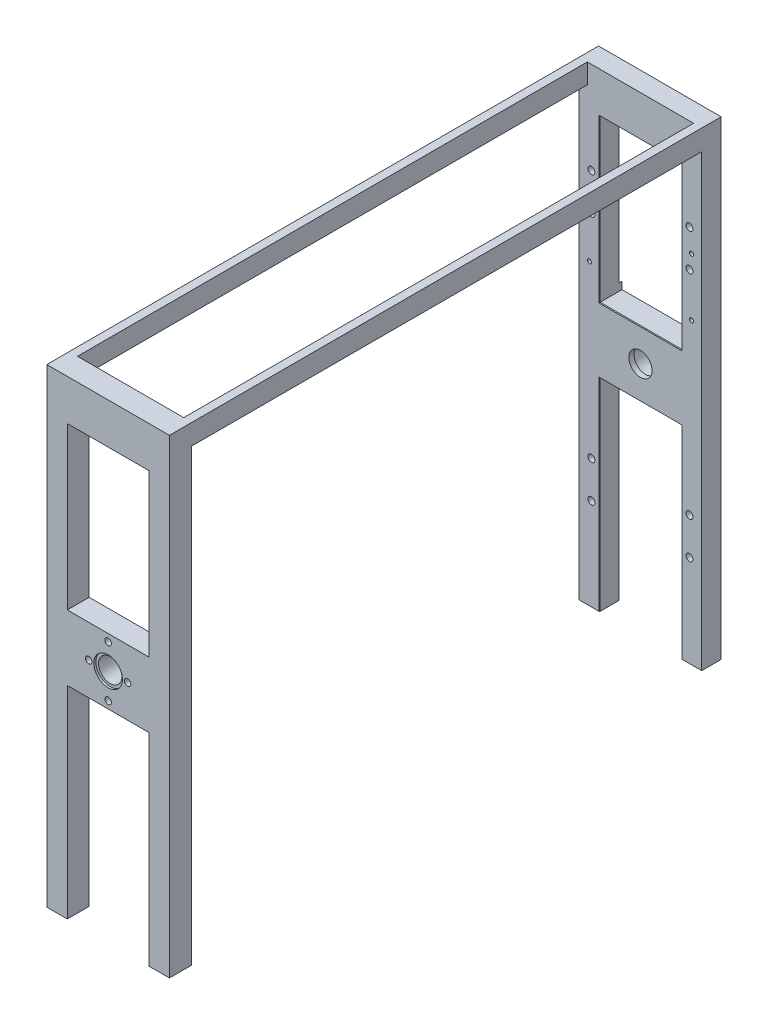
SolidWorks part; units mm, degrees
ref_plane "Front Plane" through (0, 0, 0) normal (0, 0, 1) x (1, 0, 0)
ref_plane "Top Plane" through (0, 0, 0) normal (0, 1, 0) x (1, 0, 0)
ref_plane "Right Plane" through (0, 0, 0) normal (1, 0, 0) x (0, 0, -1)
sketch "Sketch1" plane through (0, 0, 0) normal (0, 0, 1) x (1, 0, 0)
  line L1 (-30, -115) -> (30, -115)
  line L2 (-30, -115) -> (-30, 115)
  line L3 (-30, 115) -> (30, 115)
  line L4 (30, -115) -> (30, 115)
  line L5 (-30, -115) -> (30, 115) construction
  line L6 (-30, 115) -> (30, -115) construction
  point P0 (0, 0)
  dimension "D1" = 60
  dimension "D2" = 230
extrude "Boss-Extrude1" add sketch "Sketch1" along normal blind 11 from offset 8 offset against normal yes
sketch "Sketch2" plane through (0, 0, 0) normal (0, 0, 1) x (1, 0, 0)
  line L0 (30, -115) -> (30, 115) construction
  line L1 (-20, -16) -> (20, -16)
  line L2 (-20, -16) -> (-20, -115)
  line L3 (-20, -115) -> (20, -115)
  line L4 (20, -16) -> (20, -115)
  line L5 (-30, 115) -> (-30, -115) construction
  line L6 (-30, -115) -> (30, -115) construction
  dimension "D1" = 10
  dimension "D2" = 10
  dimension "D3" = 0
  dimension "D4" = 99
extrude "Cut-Extrude1" cut sketch "Sketch2" along normal through all both and the other way through all
sketch "Sketch3" plane through (0, 0, 0) normal (0, 0, 1) x (1, 0, 0)
  line L0 (30, -115) -> (30, 115) construction
  line L1 (-20, 16) -> (20, 16)
  line L2 (-20, 16) -> (-20, 95)
  line L3 (-20, 95) -> (20, 95)
  line L4 (20, 16) -> (20, 95)
  line L5 (-20, 16) -> (20, 95) construction
  line L6 (-20, 95) -> (20, 16) construction
  point P0 (0, 55.5)
  dimension "D1" = 40
  dimension "D2" = 10
  dimension "D3" = 16
  dimension "D4" = 79
extrude "Cut-Extrude2" cut sketch "Sketch3" along normal through all both and the other way through all
ref_plane "Plane16" through (0, 0, 252.5) normal (0, 0, 1) x (1, 0, 0)
sketch "Sketch4" plane through (0, 0, 252.5) normal (0, 0, 1) x (1, 0, 0)
  line L1 (-30, -115) -> (30, -115)
  line L2 (-30, -115) -> (-30, 115)
  line L3 (-30, 115) -> (30, 115)
  line L4 (30, -115) -> (30, 115)
  line L5 (-30, -115) -> (30, 115) construction
  line L6 (-30, 115) -> (30, -115) construction
  point P0 (0, 0)
  dimension "D1" = 60
  dimension "D2" = 230
extrude "Boss-Extrude3" add sketch "Sketch4" along normal blind 11 separate body
sketch "Sketch6" plane through (0, 0, 263.5) normal (0, 0, 1) x (1, 0, 0)
  line L1 (-20, 16) -> (20, 16)
  line L2 (-20, 16) -> (-20, 95)
  line L3 (-20, 95) -> (20, 95)
  line L4 (20, 16) -> (20, 95)
  line L5 (-20, 16) -> (20, 95) construction
  line L6 (-20, 95) -> (20, 16) construction
  line L7 (30, -115) -> (30, 115) construction
  point P0 (0, 55.5)
  dimension "D1" = 40
  dimension "D2" = 10
  dimension "D3" = 16
  dimension "D4" = 79
extrude "Cut-Extrude3" cut sketch "Sketch6" against normal through all both and the other way through all
sketch "Sketch7" plane through (0, 0, 252.5) normal (0, 0, 1) x (1, 0, 0)
  line L0 (-20, -16) -> (20, -16)
  line L1 (-20, -16) -> (-20, -115)
  line L2 (-20, -115) -> (20, -115)
  line L3 (20, -16) -> (20, -115)
  line L4 (30, -115) -> (30, 115) construction
  line L5 (-30, -115) -> (30, -115) construction
  dimension "D1" = 99
  dimension "D2" = 10
  dimension "D3" = 40
  dimension "D4" = 0
extrude "Cut-Extrude4" cut sketch "Sketch7" along normal through all both and the other way through all
sketch "Sketch8" plane through (0, 0, 3) normal (0, 0, 1) x (1, 0, 0)
  line L0 (-30, 115) -> (-30, -115) construction
  line L1 (-30, 105) -> (-26, 105)
  line L2 (-30, 105) -> (-30, 115)
  line L3 (-30, 115) -> (-26, 115)
  line L4 (-26, 105) -> (-26, 115)
  line L5 (0, -126.5) -> (0, 126.5) construction
  line L6 (26, 105) -> (26, 115)
  line L7 (30, 115) -> (26, 115)
  line L8 (30, 105) -> (30, 115)
  line L9 (30, 105) -> (26, 105)
  dimension "D1" = 4
  dimension "D2" = 10
  dimension "D3" = 105
extrude "Boss-Extrude4" add sketch "Sketch8" along direction (0, 0, -1) on the side of the normal up to surface (249.5 mm away)
sketch "Sketch9" plane through (0, 0, 252.5) normal (0, 0, 1) x (1, 0, 0)
  circle A0 centre (0, 0) radius 6.5
extrude "Cut-Extrude13" cut sketch "Sketch9" along normal through all both and the other way through all
sketch "Sketch13" plane through (0, 0, 252.5) normal (0, 0, -1) x (-1, 0, 0)
  circle A0 centre (0, 0) radius 7
extrude "Cut-Extrude15" cut sketch "Sketch13" against normal blind 1 from offset 10 offset against normal yes
sketch "Sketch14" plane through (0, 0, -8) normal (0, 0, -1) x (-1, 0, 0)
  circle A0 centre (0, 0) radius 7
extrude "Cut-Extrude16" cut sketch "Sketch14" against normal blind 1
sketch "Sketch15" plane through (0, 0, 263.5) normal (0, 0, 1) x (1, 0, 0)
  line L0 (0, -126.5) -> (0, 126.5) construction
  line L1 (33, 0) -> (-33, 0) construction
  circle A4 centre (9.5, 0) radius 1.6
  circle A5 centre (-9.5, 0) radius 1.6
  circle A6 centre (0, 12.5) radius 1.6
  circle A7 centre (0, -12.5) radius 1.6
  point P11 (0, 0)
extrude "Cut-Extrude17" cut sketch "Sketch15" against normal up to next
sketch "Sketch17" plane through (0, 0, -8) normal (0, 0, -1) x (-1, 0, 0)
  line L0 (0, 126.5) -> (0, -126.5) construction
  line L1 (20, 62) -> (30, 62)
  line L2 (20, 62) -> (20, 28)
  line L3 (20, 28) -> (30, 28)
  line L4 (30, 62) -> (30, 28)
  line L5 (20, 62) -> (30, 28) construction
  line L6 (20, 28) -> (30, 62) construction
  line L7 (-20, 28) -> (-30, 28)
  line L8 (-30, 62) -> (-30, 28)
  line L9 (-20, 62) -> (-30, 62)
  line L10 (-20, 62) -> (-20, 28)
  point P0 (25, 45)
  dimension "D1" = 45
  dimension "D2" = 25
  dimension "D3" = 10
  dimension "D4" = 34
extrude "Boss-Extrude5" add sketch "Sketch17" along normal blind 6
sketch "Sketch18" plane through (0, 0, -14) normal (0, 0, -1) x (-1, 0, 0)
  line L0 (-30, 28) -> (-20, 28) construction
  line L1 (-20, 62) -> (-30, 62) construction
  line L2 (-30, -115) -> (-30, 28) construction
  line L3 (-20, 16) -> (-20, 28) construction
  line L4 (0, 126.5) -> (0, -126.5) construction
  line L5 (-30, 28) -> (-20, 28) construction
  line L6 (20, 16) -> (-20, 16) construction
  circle A0 centre (-25, 59.2) radius 1
  circle A1 centre (-25, 31) radius 1
  circle A2 centre (25, 59.2) radius 1
  circle A3 centre (25, 31) radius 1
  dimension "D5" = 28.2
  dimension "D1" = 28
  dimension "D2" = 34
  dimension "D3" = 10
  dimension "D4" = 30
  dimension "D6" = 12
  dimension "D7" = 15
extrude "Cut-Extrude18" cut sketch "Sketch18" against normal up to next
chamfer "Chamfer1" distance 0.3 angle 45 1 edges at (-30, -5, 252.5)
chamfer "Chamfer2" distance 0.3 angle 45 1 edges at (30, -5, 252.5)
chamfer "Chamfer3" distance 0.3 angle 45 2 edges at (-26, 105, 127.75) (26, 105, 127.75)
chamfer "Chamfer4" distance 0.3 angle 45 7 edges at (0, 16, 3) (-20, 55.5, 3) (0, 95, 3) (20, 55.5, 3) (20, -65.5, 3) (0, -16, 3) (-20, -65.5, 3)
chamfer "Chamfer5" distance 0.3 angle 45 7 edges at (-20, -65.5, 252.5) (20, -65.5, 252.5) (0, -16, 252.5) (0, 95, 252.5) (-20, 55.5, 252.5) (0, 16, 252.5) (20, 55.5, 252.5)
sketch "Sketch19" plane through (0, 0, 0) normal (0, 0, 1) x (1, 0, 0)
  circle A0 centre (0, 0) radius 10
  circle A1 centre (0, 0) radius 6.5
extrude "Upper_Bearing_Housing_Extension" add sketch "Sketch19" along normal blind 3.9 from offset 248.7
sketch "Sketch20" plane through (0, 0, 0) normal (0, 0, 1) x (1, 0, 0)
  circle A0 centre (0, 0) radius 6.51
  circle A1 centre (0, 0) radius 5.7
extrude "Lower_Bearing_Outer_Race_Shoulder" add sketch "Sketch20" along normal blind 2.5 from offset 0.5
sketch "Sketch21" plane through (0, 0, 0) normal (0, 0, 1) x (1, 0, 0)
  circle A0 centre (0, 0) radius 6.51
  circle A1 centre (0, 0) radius 5.7
extrude "Upper_Bearing_Outer_Race_Shoulder" add sketch "Sketch21" along normal blind 8.8 from offset 253.7
sketch "Sketch22" plane through (0, 0, 3) normal (0, 0, 1) x (1, 0, 0)
  circle A0 centre (-24, -52) radius 1.7
  circle A1 centre (-24, 52) radius 1.7
  circle A2 centre (24, -52) radius 1.7
  circle A3 centre (24, 52) radius 1.7
extrude "Four_Stage_Support_D3p4" cut sketch "Sketch22" against normal blind 17.01
sketch "Sketch23" plane through (0, 0, -8) normal (0, 0, -1) x (-1, 0, 0)
  circle A0 centre (-7.188, 4.15) radius 1
  circle A1 centre (7.188, 4.15) radius 1
  circle A2 centre (0, -8.3) radius 1
extrude "Lower_Retainer_M2_Envelope" cut sketch "Sketch23" against normal blind 3.2
sketch "Sketch24" plane through (0, 0, 248.7) normal (0, 0, -1) x (-1, 0, 0)
  circle A0 centre (-7.188, 4.15) radius 1
  circle A1 centre (7.188, 4.15) radius 1
  circle A2 centre (0, -8.3) radius 1
extrude "Upper_Retainer_M2_Envelope" cut sketch "Sketch24" against normal blind 3.2
sketch "Sketch25" plane through (0, 0, -14) normal (0, 0, -1) x (-1, 0, 0)
  circle A0 centre (0, 0) radius 130
  circle A1 centre (0, 0) radius 28
extrude "Pitch_Linkage_Underside_Clearance_R28_Up7p5" cut sketch "Sketch25" against normal blind 7.5
sketch "Sketch26" plane through (0, 0, 3) normal (0, 0, 1) x (1, 0, 0)
  circle A0 centre (-24, -70) radius 1.7
  circle A1 centre (-24, 70) radius 1.7
  circle A2 centre (24, -70) radius 1.7
  circle A3 centre (24, 70) radius 1.7
extrude "Four_Link_Frame_Support_Holes_Y70" cut sketch "Sketch26" against normal blind 9.51
